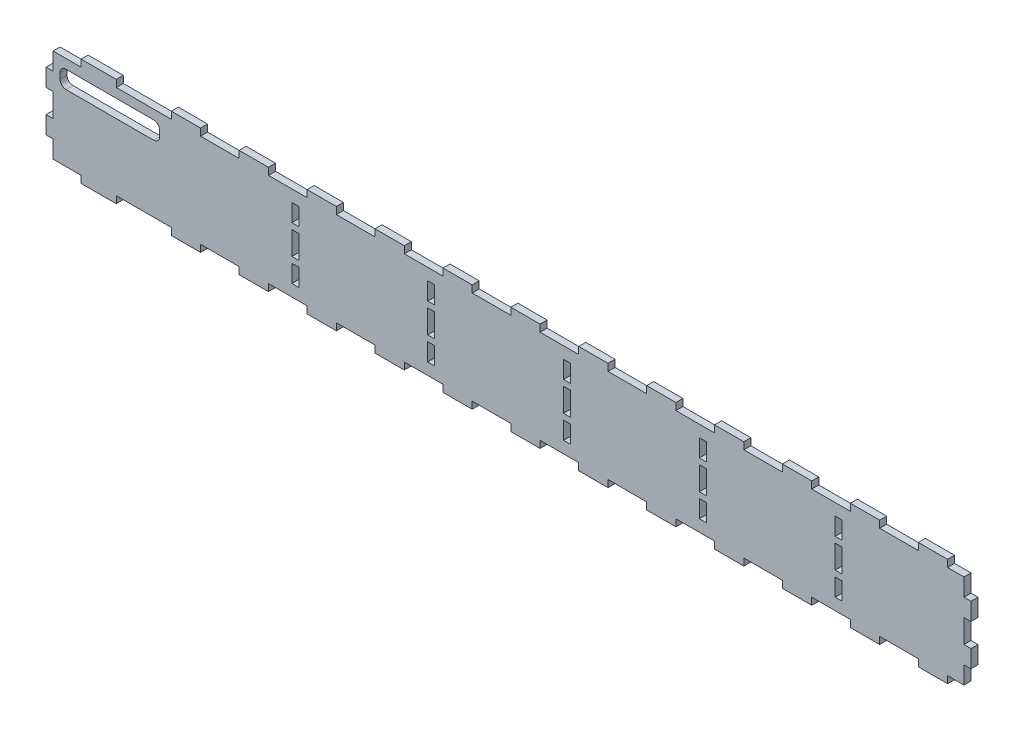
SolidWorks part; units mm, degrees
material "Acrylic (Medium-high impact)"
ref_plane "Front Plane" through (0, 0, 0) normal (0, 0, 1) x (1, 0, 0)
ref_plane "Top Plane" through (0, 0, 0) normal (0, 1, 0) x (1, 0, 0)
ref_plane "Right Plane" through (0, 0, 0) normal (1, 0, 0) x (0, 0, -1)
sketch "Sketch1" plane through (0, 0, 0) normal (0, 0, 1) x (1, 0, 0)
  line L1 (395, 40) -> (-395, 40)
  line L2 (395, 40) -> (395, -40)
  line L3 (395, -40) -> (-395, -40)
  line L4 (-395, 40) -> (-395, -40)
  line L5 (395, 40) -> (-395, -40) construction
  line L6 (395, -40) -> (-395, 40) construction
  point P0 (0, 0)
  dimension "D1" = 790
  dimension "D2" = 80
extrude "Boss-Extrude1" add sketch "Sketch1" along normal blind 6
sketch "Sketch2" plane through (0, 40, 0) normal (0, 1, 0) x (1, 0, 0)
  line L0 (395, 0) -> (-395, 0) construction
  line L1 (375, 0) -> (350, 0)
  line L2 (375, 0) -> (375, -6)
  line L3 (375, -6) -> (350, -6)
  line L4 (350, 0) -> (350, -6)
  line L5 (395, -6) -> (-395, -6) construction
  line L6 (317, 0) -> (292, 0)
  line L7 (317, 0) -> (317, -6)
  line L8 (317, -6) -> (292, -6)
  line L9 (292, 0) -> (292, -6)
  line L10 (259, 0) -> (234, 0)
  line L11 (259, 0) -> (259, -6)
  line L12 (259, -6) -> (234, -6)
  line L13 (234, 0) -> (234, -6)
  line L14 (201, 0) -> (176, 0)
  line L15 (201, 0) -> (201, -6)
  line L16 (201, -6) -> (176, -6)
  line L17 (176, 0) -> (176, -6)
  line L18 (143, 0) -> (118, 0)
  line L19 (143, 0) -> (143, -6)
  line L20 (143, -6) -> (118, -6)
  line L21 (118, 0) -> (118, -6)
  line L22 (85, 0) -> (60, 0)
  line L23 (85, 0) -> (85, -6)
  line L24 (85, -6) -> (60, -6)
  line L25 (60, 0) -> (60, -6)
  line L26 (27, 0) -> (2, 0)
  line L27 (27, 0) -> (27, -6)
  line L28 (27, -6) -> (2, -6)
  line L29 (2, 0) -> (2, -6)
  line L30 (-31, 0) -> (-56, 0)
  line L31 (-31, 0) -> (-31, -6)
  line L32 (-31, -6) -> (-56, -6)
  line L33 (-56, 0) -> (-56, -6)
  line L34 (-89, 0) -> (-114, 0)
  line L35 (-89, 0) -> (-89, -6)
  line L36 (-89, -6) -> (-114, -6)
  line L37 (-114, 0) -> (-114, -6)
  line L38 (-147, 0) -> (-172, 0)
  line L39 (-147, 0) -> (-147, -6)
  line L40 (-147, -6) -> (-172, -6)
  line L41 (-172, 0) -> (-172, -6)
  line L42 (-205, 0) -> (-230, 0)
  line L43 (-205, 0) -> (-205, -6)
  line L44 (-205, -6) -> (-230, -6)
  line L45 (-230, 0) -> (-230, -6)
  line L46 (-263, 0) -> (-288, 0)
  line L47 (-263, 0) -> (-263, -6)
  line L48 (-263, -6) -> (-288, -6)
  line L49 (-288, 0) -> (-288, -6)
  dimension "D1" = 20
  dimension "D2" = 25
  dimension "D3" = 12
extrude "Boss-Extrude2" add sketch "Sketch2" along normal blind 6
sketch "Sketch3" plane through (0, -40, 0) normal (0, -1, 0) x (1, 0, 0)
  line L0 (-263, 6) -> (-263, 0) construction
  line L1 (-263, 0) -> (-288, 0) construction
  line L2 (-288, 0) -> (-288, 6) construction
  line L3 (-288, 6) -> (-263, 6) construction
  line L4 (-205, 6) -> (-205, 0) construction
  line L5 (-205, 0) -> (-230, 0) construction
  line L6 (-230, 0) -> (-230, 6) construction
  line L7 (-230, 6) -> (-205, 6) construction
  line L8 (-147, 6) -> (-147, 0) construction
  line L9 (-147, 0) -> (-172, 0) construction
  line L10 (-172, 0) -> (-172, 6) construction
  line L11 (-172, 6) -> (-147, 6) construction
  line L12 (-89, 6) -> (-89, 0) construction
  line L13 (-89, 0) -> (-114, 0) construction
  line L14 (-114, 0) -> (-114, 6) construction
  line L15 (-114, 6) -> (-89, 6) construction
  line L16 (-31, 6) -> (-31, 0) construction
  line L17 (-31, 0) -> (-56, 0) construction
  line L18 (-56, 0) -> (-56, 6) construction
  line L19 (-56, 6) -> (-31, 6) construction
  line L20 (27, 6) -> (27, 0) construction
  line L21 (27, 0) -> (2, 0) construction
  line L22 (2, 0) -> (2, 6) construction
  line L23 (2, 6) -> (27, 6) construction
  line L24 (85, 6) -> (85, 0) construction
  line L25 (85, 0) -> (60, 0) construction
  line L26 (60, 0) -> (60, 6) construction
  line L27 (60, 6) -> (85, 6) construction
  line L28 (143, 6) -> (143, 0) construction
  line L29 (143, 0) -> (118, 0) construction
  line L30 (118, 0) -> (118, 6) construction
  line L31 (118, 6) -> (143, 6) construction
  line L32 (201, 6) -> (201, 0) construction
  line L33 (201, 0) -> (176, 0) construction
  line L34 (176, 0) -> (176, 6) construction
  line L35 (176, 6) -> (201, 6) construction
  line L36 (259, 6) -> (259, 0) construction
  line L37 (259, 0) -> (234, 0) construction
  line L38 (234, 0) -> (234, 6) construction
  line L39 (234, 6) -> (259, 6) construction
  line L40 (317, 6) -> (317, 0) construction
  line L41 (317, 0) -> (292, 0) construction
  line L42 (292, 0) -> (292, 6) construction
  line L43 (292, 6) -> (317, 6) construction
  line L44 (375, 6) -> (375, 0) construction
  line L45 (375, 0) -> (350, 0) construction
  line L46 (350, 0) -> (350, 6) construction
  line L47 (350, 6) -> (375, 6) construction
  line L48 (-263, 6) -> (-263, 0)
  line L49 (-263, 0) -> (-288, 0)
  line L50 (-288, 0) -> (-288, 6)
  line L51 (-288, 6) -> (-263, 6)
  line L52 (-205, 6) -> (-205, 0)
  line L53 (-205, 0) -> (-230, 0)
  line L54 (-230, 0) -> (-230, 6)
  line L55 (-230, 6) -> (-205, 6)
  line L56 (-147, 6) -> (-147, 0)
  line L57 (-147, 0) -> (-172, 0)
  line L58 (-172, 0) -> (-172, 6)
  line L59 (-172, 6) -> (-147, 6)
  line L60 (-89, 6) -> (-89, 0)
  line L61 (-89, 0) -> (-114, 0)
  line L62 (-114, 0) -> (-114, 6)
  line L63 (-114, 6) -> (-89, 6)
  line L64 (-31, 6) -> (-31, 0)
  line L65 (-31, 0) -> (-56, 0)
  line L66 (-56, 0) -> (-56, 6)
  line L67 (-56, 6) -> (-31, 6)
  line L68 (27, 6) -> (27, 0)
  line L69 (27, 0) -> (2, 0)
  line L70 (2, 0) -> (2, 6)
  line L71 (2, 6) -> (27, 6)
  line L72 (85, 6) -> (85, 0)
  line L73 (85, 0) -> (60, 0)
  line L74 (60, 0) -> (60, 6)
  line L75 (60, 6) -> (85, 6)
  line L76 (143, 6) -> (143, 0)
  line L77 (143, 0) -> (118, 0)
  line L78 (118, 0) -> (118, 6)
  line L79 (118, 6) -> (143, 6)
  line L80 (201, 6) -> (201, 0)
  line L81 (201, 0) -> (176, 0)
  line L82 (176, 0) -> (176, 6)
  line L83 (176, 6) -> (201, 6)
  line L84 (259, 6) -> (259, 0)
  line L85 (259, 0) -> (234, 0)
  line L86 (234, 0) -> (234, 6)
  line L87 (234, 6) -> (259, 6)
  line L88 (317, 6) -> (317, 0)
  line L89 (317, 0) -> (292, 0)
  line L90 (292, 0) -> (292, 6)
  line L91 (292, 6) -> (317, 6)
  line L92 (375, 6) -> (375, 0)
  line L93 (375, 0) -> (350, 0)
  line L94 (350, 0) -> (350, 6)
  line L95 (350, 6) -> (375, 6)
  line L96 (-395, 0) -> (395, 0) construction
  line L97 (-335, 0) -> (-365, 0)
  line L98 (-335, 0) -> (-335, 6)
  line L99 (-335, 6) -> (-365, 6)
  line L100 (-365, 0) -> (-365, 6)
  line L101 (-395, 6) -> (395, 6) construction
  line L102 (-395, 6) -> (-395, 0) construction
  point P58 (-395, 3)
  dimension "D1" = 30
  dimension "D2" = 30
extrude "Boss-Extrude3" add sketch "Sketch3" along normal blind 6
sketch "Sketch4" plane through (0, 0, 0) normal (0, 0, -1) x (-1, 0, 0)
  line L0 (288, 40) -> (395, 40) construction
  line L1 (378, 17) -> (303, 17)
  line L2 (383, 22) -> (383, 27)
  line L3 (378, 32) -> (303, 32)
  line L4 (298, 22) -> (298, 27)
  line L5 (395, 40) -> (395, -40) construction
  arc A0 (378, 17) -> (383, 22) centre (378, 22) ccw
  arc A1 (303, 32) -> (298, 27) centre (303, 27) ccw
  arc A2 (303, 17) -> (298, 22) centre (303, 22) cw
  arc A3 (383, 27) -> (378, 32) centre (378, 27) ccw
  point P10 (383, 17)
  point P13 (298, 32)
  point P18 (383, 32)
  dimension "D5" = 5
  dimension "D1" = 85
  dimension "D2" = 15
  dimension "D3" = 8
  dimension "D4" = 12
extrude "Cut-Extrude1" cut sketch "Sketch4" against normal blind 6
sketch "Sketch5" plane through (-395, 0, 0) normal (-1, 0, 0) x (0, 0, 1)
  line L1 (6, 40) -> (6, -40) construction
  line L2 (0, -40) -> (6, -40)
  line L3 (0, -40) -> (0, -25)
  line L4 (0, -25) -> (6, -25)
  line L7 (6, -40) -> (6, -25)
  line L8 (0, 40) -> (0, -40) construction
  line L9 (6, -10) -> (0, -10)
  line L10 (6, -10) -> (6, 10)
  line L12 (6, 10) -> (0, 10)
  line L13 (0, -10) -> (0, 10)
  line L15 (0, 40) -> (6, 40)
  line L16 (0, 40) -> (0, 25)
  line L17 (0, 25) -> (6, 25)
  line L18 (6, 40) -> (6, 25)
  dimension "D1" = 15
  dimension "D2" = 15
  dimension "D3" = 15
  dimension "D4" = 15
extrude "Cut-Extrude2" cut sketch "Sketch5" against normal blind 6
sketch "Sketch7" plane through (395, 0, 0) normal (1, 0, 0) x (0, 0, -1)
  line L0 (0, 40) -> (0, 25) construction
  line L1 (0, 25) -> (-6, 25) construction
  line L2 (-6, 25) -> (-6, 40) construction
  line L3 (-6, 40) -> (0, 40) construction
  line L4 (-6, -10) -> (-6, 10) construction
  line L5 (-6, 10) -> (0, 10) construction
  line L6 (0, 10) -> (0, -10) construction
  line L7 (0, -10) -> (-6, -10) construction
  line L8 (0, -25) -> (0, -40) construction
  line L9 (0, -40) -> (-6, -40) construction
  line L10 (-6, -40) -> (-6, -25) construction
  line L11 (-6, -25) -> (0, -25) construction
  line L12 (0, 40) -> (0, 25)
  line L13 (0, 25) -> (-6, 25)
  line L14 (-6, 25) -> (-6, 40)
  line L15 (-6, 40) -> (0, 40)
  line L16 (-6, -10) -> (-6, 10)
  line L17 (-6, 10) -> (0, 10)
  line L18 (0, 10) -> (0, -10)
  line L19 (0, -10) -> (-6, -10)
  line L20 (0, -25) -> (0, -40)
  line L21 (0, -40) -> (-6, -40)
  line L22 (-6, -40) -> (-6, -25)
  line L23 (-6, -25) -> (0, -25)
extrude "Cut-Extrude3" cut sketch "Sketch7" against normal blind 6
sketch "Sketch8" plane through (0, 40, 0) normal (0, 1, 0) x (1, 0, 0)
  line L4 (-335, -6) -> (-335, 0)
  line L5 (-365, -6) -> (-335, -6)
  line L6 (-365, 0) -> (-365, -6)
  line L7 (-335, 0) -> (-365, 0)
  line L8 (-335, -6) -> (-335, 0)
  line L9 (-365, -6) -> (-335, -6)
  line L10 (-365, 0) -> (-365, -6)
  line L11 (-335, 0) -> (-365, 0)
  dimension "D1" = 0
extrude "Boss-Extrude6" add sketch "Sketch8" along normal blind 6
sketch "Sketch9" plane through (0, 0, 6) normal (0, 0, 1) x (1, 0, 0)
  line L0 (163, -10) -> (169, -10)
  line L1 (169, -10) -> (169, 10)
  line L2 (169, 10) -> (163, 10)
  line L3 (163, 10) -> (163, -10)
  line L4 (279, -10) -> (285, -10)
  line L5 (285, -10) -> (285, 10)
  line L6 (285, 10) -> (279, 10)
  line L7 (279, 10) -> (279, -10)
  line L8 (279, -10) -> (285, -10)
  line L9 (285, -10) -> (285, 10)
  line L10 (285, 10) -> (279, 10)
  line L11 (279, 10) -> (279, -10)
  line L12 (169, -15) -> (163, -15)
  line L13 (169, -30) -> (169, -15)
  line L14 (163, -30) -> (169, -30)
  line L15 (163, -15) -> (163, -30)
  line L16 (169, 30) -> (163, 30)
  line L17 (169, 15) -> (169, 30)
  line L18 (163, 15) -> (169, 15)
  line L19 (163, 30) -> (163, 15)
  line L20 (47, -10) -> (53, -10)
  line L21 (53, -10) -> (53, 10)
  line L22 (53, 10) -> (47, 10)
  line L23 (47, 10) -> (47, -10)
  line L24 (53, -15) -> (47, -15)
  line L25 (53, -30) -> (53, -15)
  line L26 (47, -30) -> (53, -30)
  line L27 (47, -15) -> (47, -30)
  line L28 (285, -15) -> (279, -15)
  line L29 (285, -30) -> (285, -15)
  line L30 (279, -30) -> (285, -30)
  line L31 (279, -15) -> (279, -30)
  line L32 (285, -15) -> (279, -15)
  line L33 (285, -30) -> (285, -15)
  line L34 (279, -30) -> (285, -30)
  line L35 (279, -15) -> (279, -30)
  line L36 (285, 30) -> (279, 30)
  line L37 (285, 15) -> (285, 30)
  line L38 (279, 15) -> (285, 15)
  line L39 (279, 30) -> (279, 15)
  line L40 (285, 30) -> (279, 30)
  line L41 (285, 15) -> (285, 30)
  line L42 (279, 15) -> (285, 15)
  line L43 (279, 30) -> (279, 15)
  line L44 (53, 30) -> (47, 30)
  line L45 (53, 15) -> (53, 30)
  line L46 (47, 15) -> (53, 15)
  line L47 (47, 30) -> (47, 15)
  line L48 (-69, -10) -> (-63, -10)
  line L49 (-63, -10) -> (-63, 10)
  line L50 (-63, 10) -> (-69, 10)
  line L51 (-69, 10) -> (-69, -10)
  line L52 (-63, -15) -> (-69, -15)
  line L53 (-63, -30) -> (-63, -15)
  line L54 (-69, -30) -> (-63, -30)
  line L55 (-69, -15) -> (-69, -30)
  line L56 (-63, 30) -> (-69, 30)
  line L57 (-63, 15) -> (-63, 30)
  line L58 (-69, 15) -> (-63, 15)
  line L59 (-69, 30) -> (-69, 15)
  line L60 (-185, -10) -> (-179, -10)
  line L61 (-179, -10) -> (-179, 10)
  line L62 (-179, 10) -> (-185, 10)
  line L63 (-185, 10) -> (-185, -10)
  line L64 (-179, -15) -> (-185, -15)
  line L65 (-179, -30) -> (-179, -15)
  line L66 (-185, -30) -> (-179, -30)
  line L67 (-185, -15) -> (-185, -30)
  line L68 (-179, 30) -> (-185, 30)
  line L69 (-179, 15) -> (-179, 30)
  line L70 (-185, 15) -> (-179, 15)
  line L71 (-185, 30) -> (-185, 15)
  dimension "D1" = 0
  dimension "D2" = 0
  dimension "D3" = 0
extrude "Cut-Extrude4" cut sketch "Sketch9" against normal blind 6
